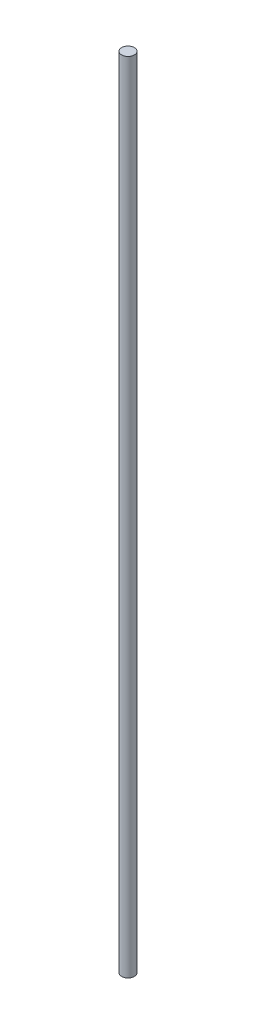
SolidWorks part; units mm, degrees
ref_plane "Front Plane" through (0, 0, 0) normal (0, 0, 1) x (1, 0, 0)
ref_plane "Top Plane" through (0, 0, 0) normal (0, 1, 0) x (1, 0, 0)
ref_plane "Right Plane" through (0, 0, 0) normal (1, 0, 0) x (0, 0, -1)
sketch "Sketch1" plane through (0, 0, 0) normal (0, 1, 0) x (1, 0, 0)
  circle A0 centre (0, 0) radius 8
  dimension "D1" = 16
extrude "Boss-Extrude1" add sketch "Sketch1" along normal blind 1000
